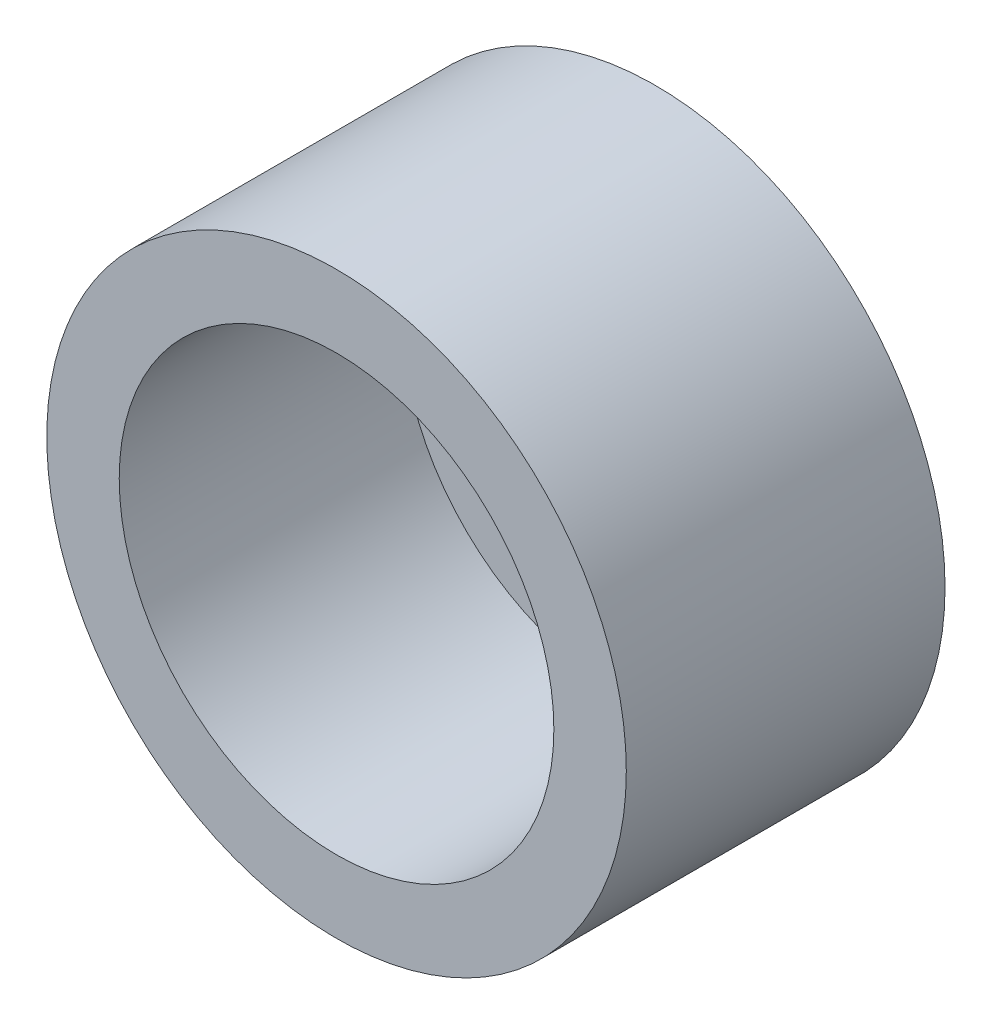
SolidWorks part; units mm, degrees
ref_plane "Plan de face" through (0, 0, 0) normal (0, 0, 1) x (1, 0, 0)
ref_plane "Plan de dessus" through (0, 0, 0) normal (0, 1, 0) x (1, 0, 0)
ref_plane "Plan de droite" through (0, 0, 0) normal (1, 0, 0) x (0, 0, -1)
sketch "Esquisse1" plane through (0, 0, 0) normal (0, 0, 1) x (1, 0, 0)
  line L0 (0, 1.1896) -> (0, -1.0883) construction
  line L1 (-1.6692, 0) -> (2.0606, 0) construction
  circle A0 centre (0, 0) radius 15
  circle A1 centre (0, 0) radius 20
  dimension "D1" = 5
  dimension "D2" = 30
extrude "Boss.-Extru.1" add sketch "Esquisse1" along normal blind 22
sketch "Esquisse5" plane through (0, 0, 0) normal (0, 0, -1) x (-1, 0, 0)
  circle A0 centre (0, 0) radius 15
  dimension "D1" = 30
extrude "Boss.-Extru.3" add sketch "Esquisse5" against normal blind 2.5
sketch "Esquisse12" plane through (0, 0, 0) normal (0, 0, -1) x (-1, 0, 0)
  circle A0 centre (0, 0) radius 4.25
  dimension "D1" = 8.5
extrude "Enlèv. mat.-Extru.2" cut sketch "Esquisse12" against normal blind 2.5
